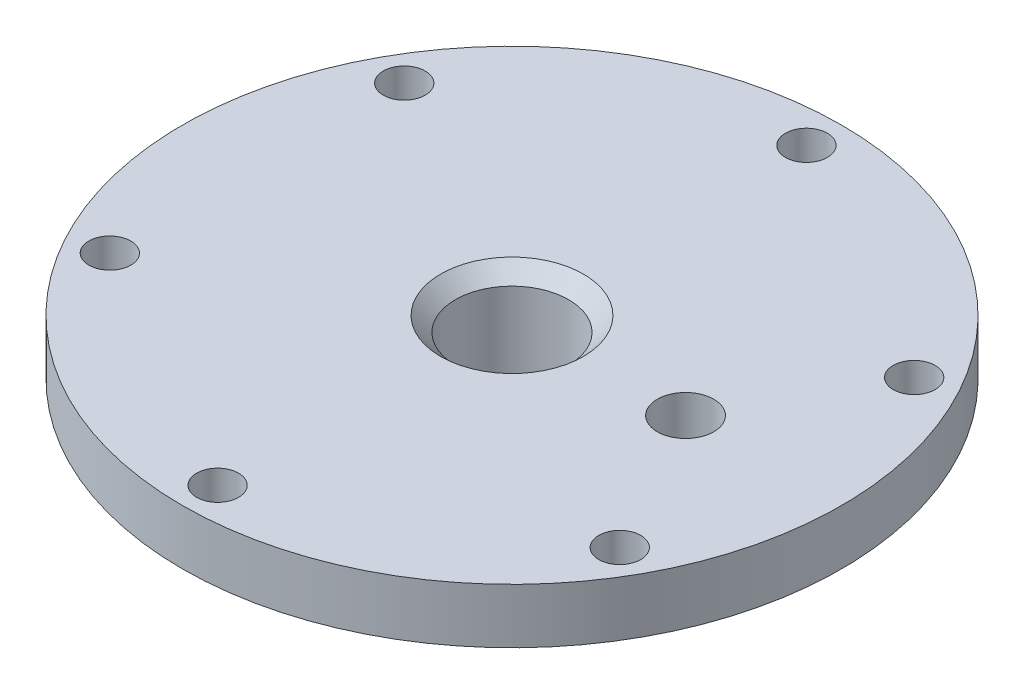
SolidWorks part; units mm, degrees
ref_plane "Front Plane" through (0, 0, 0) normal (0, 0, 1) x (1, 0, 0)
ref_plane "Top Plane" through (0, 0, 0) normal (0, 1, 0) x (1, 0, 0)
ref_plane "Right Plane" through (0, 0, 0) normal (1, 0, 0) x (0, 0, -1)
sketch "Sketch1" plane through (0, 0, 0) normal (0, 1, 0) x (1, 0, 0)
  circle A0 centre (0, 0) radius 38.1
  dimension "D1" = 76.2
extrude "Boss-Extrude1" add sketch "Sketch1" along normal blind 6.35
sketch "Sketch2" plane through (0, 0, 0) normal (0, -1, 0) x (-1, 0, 0)
  circle A0 centre (0, 0) radius 25.273
  dimension "D1" = 50.546
extrude "Boss-Extrude2" add sketch "Sketch2" along normal blind 6.35
hole_wizard "#11 (0.191) Diameter Hole1" positions "Sketch5" profile "Sketch4" hole size "#11" standard "ANSI Inch" end condition up to next
sketch "Sketch5" plane through (0, 6.35, 0) normal (0, 1, 0) x (1, 0, 0)
  line L0 (0, 0) -> (0, 42.5535) construction
  point P0 (0, 34.036)
  dimension "D1" = 34.036
sketch "Sketch4" plane through (0, 6.35, -34.036) normal (1, 0, 0) x (0, 0, 1)
  line L0 (0, 0) -> (0, 6.351)
  line L1 (0, 6.351) -> (2.4257, 6.351)
  line L2 (2.4257, 6.351) -> (2.4257, 0)
  line L5 (2.4257, 0) -> (0, 0)
  line L11 (0, -6.35) -> (0, 107.95) construction
  dimension "Thru Hole Dia." = 4.8514
  dimension "Thru Hole Depth" = 6.351
pattern_circular "CirPattern1" count 6 over 360 about axis through (0, 0, 0) along (0, 1, 0) of "#11 (0.191) Diameter Hole1"
hole_wizard "9/16-18 Tapped Hole1" positions "Sketch7" profile "Sketch6" tap size "9/16-18" standard "ANSI Inch" end condition through all
sketch "Sketch7" plane through (0, 6.35, 0) normal (0, 1, 0) x (1, 0, 0)
  point P0 (0, 0)
sketch "Sketch6" plane through (0, 6.35, 0) normal (1, 0, 0) x (0, 0, 1)
  line L0 (0, 0) -> (0, 12.7)
  line L1 (0, 12.7) -> (6.5481, 12.7)
  line L2 (6.5481, 12.7) -> (6.5481, 1.7069)
  line L3 (6.5481, 1.7069) -> (8.255, 0)
  line L5 (8.255, 0) -> (0, 0)
  line L6 (-6.5481, 1.7069) -> (-8.255, 0) construction
  line L11 (0, -6.35) -> (0, 107.95) construction
  dimension "Thru Tap Drill Dia." = 13.0962
  dimension "Thru Tap Drill Depth" = 12.7
  dimension "Near C'Sink Dia." = 16.51
  dimension "Near C'Sink Angle" = 90
cosmetic thread "Hole Thread2" parameters "D2"=14.2875
hole_wizard "F (0.257) Diameter Hole1" positions "Sketch9" profile "Sketch8" hole size "F" standard "ANSI Inch" end condition up to next
sketch "Sketch9" plane through (0, 6.35, 0) normal (0, 1, 0) x (1, 0, 0)
  line L0 (-0.465, 0) -> (37.635, 0) construction
  circle A0 centre (0, 0) radius 38.1 construction
  point P0 (20.066, 0)
  dimension "D1" = 20.066
sketch "Sketch8" plane through (20.066, 6.35, 0) normal (1, 0, 0) x (0, 0, 1)
  line L0 (0, 0) -> (0, 12.7)
  line L1 (0, 12.7) -> (3.2639, 12.7)
  line L2 (3.2639, 12.7) -> (3.2639, 0)
  line L5 (3.2639, 0) -> (0, 0)
  line L11 (0, -6.35) -> (0, 107.95) construction
  dimension "Thru Hole Dia." = 6.5278
  dimension "Thru Hole Depth" = 12.7
